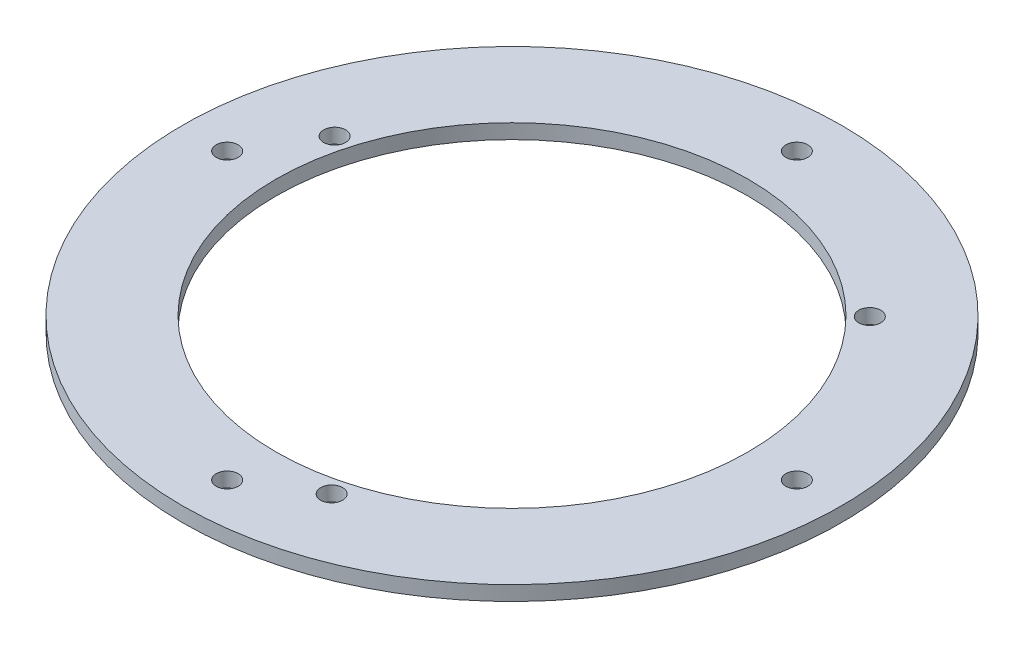
SolidWorks part; units mm, degrees
material "6061-T6 (SS)"
ref_plane "Front Plane" through (0, 0, 0) normal (0, 0, 1) x (1, 0, 0)
ref_plane "Top Plane" through (0, 0, 0) normal (0, 1, 0) x (1, 0, 0)
ref_plane "Right Plane" through (0, 0, 0) normal (1, 0, 0) x (0, 0, -1)
sketch "Sketch2" plane through (0, 0, 0) normal (0, 1, 0) x (1, 0, 0)
  line L0 (49.872, -261.8935) -> (473.872, -261.8935) construction
  line L1 (17.8971, 48.9297) -> (40.1493, 43.6512)
  line L2 (43.8664, 39.9141) -> (49.0252, 17.6338)
  line L3 (48.9297, -17.8971) -> (43.6512, -40.1493)
  line L4 (39.9141, -43.8664) -> (17.6338, -49.0252)
  line L5 (-17.8971, -48.9297) -> (-40.1493, -43.6512)
  line L6 (-43.8664, -39.9141) -> (-49.0252, -17.6338)
  line L7 (-48.9297, 17.8971) -> (-43.6512, 40.1493)
  line L8 (-39.9141, 43.8664) -> (-17.6338, 49.0252)
  line L9 (0.1397, 51.9998) -> (-0.1397, -51.9998) construction
  line L10 (-51.9998, 0.1397) -> (51.9998, -0.1397) construction
  line L11 (0, 38.8907) -> (0, -38.8907) construction
  line L12 (-38.8907, 38.8907) -> (38.8907, 38.8907) construction
  line L13 (-38.8907, 38.8907) -> (-38.8907, -38.8907) construction
  line L14 (-38.8907, -38.8907) -> (38.8907, -38.8907) construction
  line L15 (38.8907, 38.8907) -> (38.8907, -38.8907) construction
  line L16 (-38.8907, 0) -> (38.8907, 0) construction
  line L17 (-33.3234, 9.1011) -> (24.5435, 24.3084) construction
  line L18 (24.5435, 24.3084) -> (8.7799, -33.4095) construction
  line L19 (8.7799, -33.4095) -> (-33.3234, 9.1011) construction
  line L20 (24.5435, 24.3084) -> (-12.2717, -12.1542) construction
  line L21 (-33.3234, 9.1011) -> (16.6617, -4.5506) construction
  line L22 (0, 0) -> (0, 38.8907) construction
  line L23 (0, 0) -> (38.8907, 0) construction
  circle A0 centre (0, 0) radius 30 construction
  arc A3 (-17.6338, 49.0252) -> (-15.9939, 49.4792) centre (-22.1454, 68.5097) ccw
  arc A4 (0.1397, 51.9998) -> (-15.9939, 49.4792) centre (0, 0) ccw
  arc A5 (16.2596, 49.3926) -> (0.1397, 51.9998) centre (0, 0) ccw
  arc A6 (16.2596, 49.3926) -> (17.8971, 48.9297) centre (22.5132, 68.3897) ccw
  arc A7 (43.8664, 39.9141) -> (40.1493, 43.6512) centre (38.9952, 38.7862) ccw
  arc A8 (49.0252, 17.6338) -> (49.4792, 15.9939) centre (68.5097, 22.1454) ccw
  arc A9 (49.3926, -16.2596) -> (49.4792, 15.9939) centre (0, 0) ccw
  arc A10 (49.3926, -16.2596) -> (48.9297, -17.8971) centre (68.3897, -22.5132) ccw
  arc A11 (39.9141, -43.8664) -> (43.6512, -40.1493) centre (38.7862, -38.9952) ccw
  arc A12 (17.6338, -49.0252) -> (15.9939, -49.4792) centre (22.1454, -68.5097) ccw
  arc A13 (-16.2596, -49.3926) -> (15.9939, -49.4792) centre (0, 0) ccw
  arc A14 (-16.2596, -49.3926) -> (-17.8971, -48.9297) centre (-22.5132, -68.3897) ccw
  arc A15 (-43.8664, -39.9141) -> (-40.1493, -43.6512) centre (-38.9952, -38.7862) ccw
  arc A16 (-49.0252, -17.6338) -> (-49.4792, -15.9939) centre (-68.5097, -22.1454) ccw
  arc A17 (-49.3926, 16.2596) -> (-49.4792, -15.9939) centre (0, 0) ccw
  arc A18 (-49.3926, 16.2596) -> (-48.9297, 17.8971) centre (-68.3897, 22.5132) ccw
  arc A19 (-39.9141, 43.8664) -> (-43.6512, 40.1493) centre (-38.7862, 38.9952) ccw
  circle A20 centre (-38.8907, 38.8907) radius 1.5
  circle A21 centre (38.8907, 38.8907) radius 1.5
  circle A22 centre (38.8907, -38.8907) radius 1.5
  circle A23 centre (-38.8907, -38.8907) radius 1.5
  circle A24 centre (-33.3234, 9.1011) radius 1.5
  circle A25 centre (24.5435, 24.3084) radius 1.5
  circle A26 centre (8.7799, -33.4095) radius 1.5
  circle A27 centre (0, 0) radius 32.25
  circle A28 centre (0, 38.8907) radius 1.5
  circle A29 centre (38.8907, 0) radius 1.5
  circle A30 centre (0, -38.8907) radius 1.5
  circle A31 centre (-38.8907, 0) radius 1.5
  point P23 (0, 0)
  point P66 (0, 0)
  point P71 (0, 0)
  point P75 (-32.25, 13.533)
  point P76 (-33.2671, 9.3048)
  point P86 (-33.3234, 9.1011)
  dimension "D1" = 60
  dimension "D2" = 3
  dimension "D3" = 64.5
  dimension "D4" = 34.5439
  dimension "D5" = 3
  dimension "D7" = 90
  dimension "D8" = 38.8907
  dimension "D6" = 4
extrude "Boss-Extrude1" add sketch "Sketch2" along normal blind 2
sketch "Sketch3" plane through (0, 2, 0) normal (0, 1, 0) x (1, 0, 0)
  line L0 (-17.6338, 49.0252) -> (-39.9141, 43.8664) construction
  line L1 (-43.6512, 40.1493) -> (-48.9297, 17.8971) construction
  line L2 (-49.0252, -17.6338) -> (-43.8664, -39.9141) construction
  line L3 (-40.1493, -43.6512) -> (-17.8971, -48.9297) construction
  line L4 (17.6338, -49.0252) -> (39.9141, -43.8664) construction
  line L5 (43.6512, -40.1493) -> (48.9297, -17.8971) construction
  line L6 (49.0252, 17.6338) -> (43.8664, 39.9141) construction
  line L7 (40.1493, 43.6512) -> (17.8971, 48.9297) construction
  line L8 (-43.6512, 40.1493) -> (-48.9297, 17.8971)
  line L9 (-49.0252, -17.6338) -> (-43.8664, -39.9141)
  line L10 (-40.1493, -43.6512) -> (-17.8971, -48.9297)
  line L11 (17.6338, -49.0252) -> (39.9141, -43.8664)
  line L12 (43.6512, -40.1493) -> (48.9297, -17.8971)
  line L13 (49.0252, 17.6338) -> (43.8664, 39.9141)
  line L14 (40.1493, 43.6512) -> (17.8971, 48.9297)
  line L15 (-17.6338, 49.0252) -> (-39.9141, 43.8664)
  circle A0 centre (0, 0) radius 45
  arc A1 (-39.9141, 43.8664) -> (-43.6512, 40.1493) centre (-38.7862, 38.9952) ccw construction
  arc A2 (-49.3926, 16.2596) -> (-48.9297, 17.8971) centre (-68.3897, 22.5132) ccw construction
  arc A3 (-49.3926, 16.2596) -> (-49.4792, -15.9939) centre (0, 0) ccw construction
  arc A4 (-49.0252, -17.6338) -> (-49.4792, -15.9939) centre (-68.5097, -22.1454) ccw construction
  arc A5 (-43.8664, -39.9141) -> (-40.1493, -43.6512) centre (-38.9952, -38.7862) ccw construction
  arc A6 (-16.2596, -49.3926) -> (-17.8971, -48.9297) centre (-22.5132, -68.3897) ccw construction
  arc A7 (-16.2596, -49.3926) -> (15.9939, -49.4792) centre (0, 0) ccw construction
  arc A8 (17.6338, -49.0252) -> (15.9939, -49.4792) centre (22.1454, -68.5097) ccw construction
  arc A9 (39.9141, -43.8664) -> (43.6512, -40.1493) centre (38.7862, -38.9952) ccw construction
  arc A10 (49.3926, -16.2596) -> (48.9297, -17.8971) centre (68.3897, -22.5132) ccw construction
  arc A11 (49.3926, -16.2596) -> (49.4792, 15.9939) centre (0, 0) ccw construction
  arc A12 (49.0252, 17.6338) -> (49.4792, 15.9939) centre (68.5097, 22.1454) ccw construction
  arc A13 (43.8664, 39.9141) -> (40.1493, 43.6512) centre (38.9952, 38.7862) ccw construction
  arc A14 (16.2596, 49.3926) -> (17.8971, 48.9297) centre (22.5132, 68.3897) ccw construction
  arc A15 (16.2596, 49.3926) -> (-15.9939, 49.4792) centre (0, 0) ccw construction
  arc A16 (-17.6338, 49.0252) -> (-15.9939, 49.4792) centre (-22.1454, 68.5097) ccw construction
  arc A17 (-39.9141, 43.8664) -> (-43.6512, 40.1493) centre (-38.7862, 38.9952) ccw
  arc A18 (-49.3926, 16.2596) -> (-48.9297, 17.8971) centre (-68.3897, 22.5132) ccw
  arc A19 (-49.3926, 16.2596) -> (-49.4792, -15.9939) centre (0, 0) ccw
  arc A20 (-49.0252, -17.6338) -> (-49.4792, -15.9939) centre (-68.5097, -22.1454) ccw
  arc A21 (-43.8664, -39.9141) -> (-40.1493, -43.6512) centre (-38.9952, -38.7862) ccw
  arc A22 (-16.2596, -49.3926) -> (-17.8971, -48.9297) centre (-22.5132, -68.3897) ccw
  arc A23 (-16.2596, -49.3926) -> (15.9939, -49.4792) centre (0, 0) ccw
  arc A24 (17.6338, -49.0252) -> (15.9939, -49.4792) centre (22.1454, -68.5097) ccw
  arc A25 (39.9141, -43.8664) -> (43.6512, -40.1493) centre (38.7862, -38.9952) ccw
  arc A26 (49.3926, -16.2596) -> (48.9297, -17.8971) centre (68.3897, -22.5132) ccw
  arc A27 (49.3926, -16.2596) -> (49.4792, 15.9939) centre (0, 0) ccw
  arc A28 (49.0252, 17.6338) -> (49.4792, 15.9939) centre (68.5097, 22.1454) ccw
  arc A29 (43.8664, 39.9141) -> (40.1493, 43.6512) centre (38.9952, 38.7862) ccw
  arc A30 (16.2596, 49.3926) -> (17.8971, 48.9297) centre (22.5132, 68.3897) ccw
  arc A31 (16.2596, 49.3926) -> (-15.9939, 49.4792) centre (0, 0) ccw
  arc A32 (-17.6338, 49.0252) -> (-15.9939, 49.4792) centre (-22.1454, 68.5097) ccw
  dimension "D1" = 90
extrude "Cut-Extrude1" cut sketch "Sketch3" against normal through all
